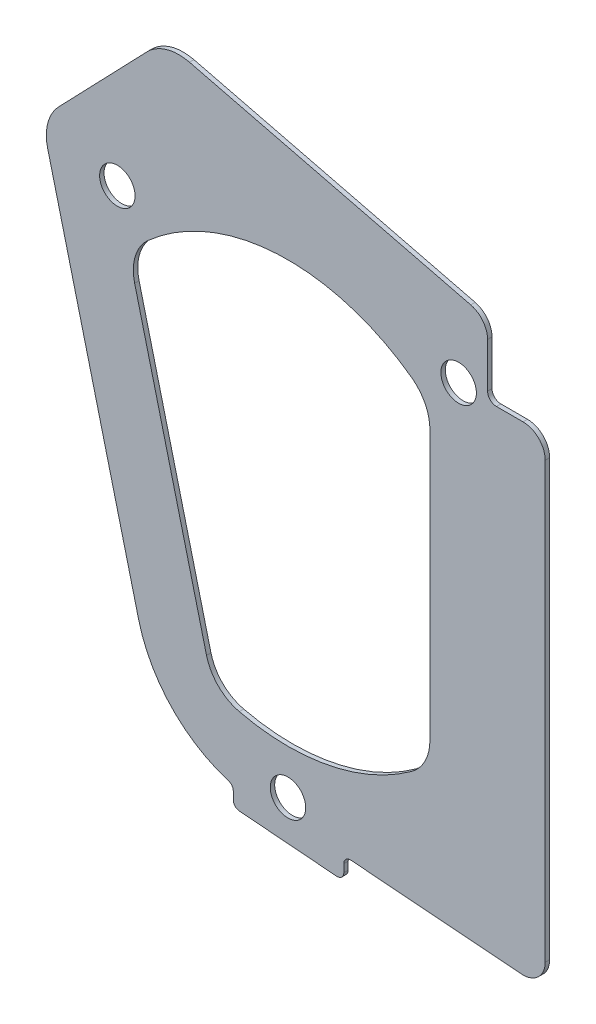
SolidWorks part; units mm, degrees
ref_plane "Front Plane" through (0, 0, 0) normal (0, 0, 1) x (1, 0, 0)
ref_plane "Top Plane" through (0, 0, 0) normal (0, 1, 0) x (1, 0, 0)
ref_plane "Right Plane" through (0, 0, 0) normal (1, 0, 0) x (0, 0, -1)
sketch "Sketch1" plane through (0, 0, 0) normal (0, 0, 1) x (1, 0, 0)
  line L0 (-38.475, 42.7308) -> (0, 0) construction
  line L1 (0, 0) -> (0, 57.5) construction
  line L4 (32, 30.3686) -> (32, -30.3686)
  line L5 (-12.3399, -62.3721) -> (-12.3399, -64.1252)
  line L6 (-10.9599, -65.6204) -> (10.9599, -67.3796)
  line L7 (12.5799, -65.8844) -> (12.5799, -64.1313)
  line L8 (14.1967, -62.6359) -> (52.6107, -65.6359)
  line L9 (58, -60.6511) -> (58, 37.3641)
  line L10 (53, 42.3641) -> (47, 42.3641)
  line L11 (45, 44.3641) -> (45, 54.4497)
  line L12 (41.2, 59.3036) -> (-22.2032, 74.9785)
  line L14 (-12.3399, -61.2431) -> (-9.4422, -62.0196) construction
  line L15 (-31.8103, 72.2031) -> (-51.6964, 51.5287)
  line L16 (-54.1884, 42.1617) -> (-33.6727, -39.5692)
  line L17 (-34.5729, 25.6286) -> (-18.3707, -38.9182)
  circle A0 centre (0, 0) radius 57.5 construction
  arc A2 (27.8667, 38.4669) -> (-31.5069, 35.5467) centre (0, 0) ccw
  circle A3 centre (0, -57.5) radius 4
  circle A4 centre (-38.475, 42.7308) radius 4
  circle A5 centre (38.475, 42.7308) radius 4
  arc A6 (-33.6727, -39.5692) -> (-13.3988, -60.9385) centre (-4.5754, -32.2653) ccw
  circle A7 centre (0, 0) radius 47.5 construction
  arc A9 (32, -30.3686) -> (27.8667, -38.4669) centre (22, -30.3686) cw
  arc A10 (32, 30.3686) -> (27.8667, 38.4669) centre (22, 30.3686) ccw
  arc A11 (-10.9841, -46.2126) -> (27.8667, -38.4669) centre (0, 0) ccw
  arc A12 (-18.3707, -38.9182) -> (-10.9841, -46.2126) centre (-8.6716, -36.4836) ccw
  arc A13 (-34.5729, 25.6286) -> (-31.5069, 35.5467) centre (-24.8738, 28.0632) cw
  arc A14 (-22.2032, 74.9785) -> (-31.8103, 72.2031) centre (-24.6032, 65.2707) ccw
  arc A15 (-51.6964, 51.5287) -> (-54.1884, 42.1617) centre (-44.4893, 44.5964) ccw
  arc A16 (58, 37.3641) -> (53, 42.3641) centre (53, 37.3641) ccw
  arc A17 (45, 54.4497) -> (41.2, 59.3036) centre (40, 54.4497) ccw
  arc A18 (47, 42.3641) -> (45, 44.3641) centre (47, 44.3641) cw
  arc A19 (52.6107, -65.6359) -> (58, -60.6511) centre (53, -60.6511) ccw
  arc A20 (12.5799, -64.1313) -> (14.1967, -62.6359) centre (14.0799, -64.1313) cw
  arc A21 (10.9599, -67.3796) -> (12.5799, -65.8844) centre (11.0799, -65.8844) ccw
  arc A22 (-12.3399, -64.1252) -> (-10.9599, -65.6204) centre (-10.8399, -64.1252) ccw
  arc A23 (-12.3399, -62.3721) -> (-13.3988, -60.9385) centre (-13.8399, -62.3721) ccw
  point P30 (0, -66.5)
  point P39 (-17.007, -44.351)
  point P44 (-27.808, 76.3641)
  point P47 (-55.5373, 47.5355)
  point P50 (58, 42.3641)
  point P53 (45, 58.3641)
  point P56 (45, 42.3641)
  point P59 (58, -66.0568)
  point P62 (12.5799, -62.5096)
  point P65 (12.5799, -67.5096)
  point P68 (-12.3399, -65.5096)
  dimension "D1" = 115
  dimension "D4" = 8
  dimension "D8" = 58
  dimension "D9" = 10
  dimension "D18" = 30
  dimension "D23" = 10
  dimension "D24" = 10
  dimension "D25" = 5
  dimension "D26" = 2
  dimension "D27" = 5
  dimension "D28" = 1.5
  dimension "D5" = 42
  dimension "D6" = 5
  dimension "D7" = 32
  dimension "D2" = 25
  dimension "D10" = 13
  dimension "D11" = 108
  dimension "D12" = 9
  dimension "D13" = 2
  dimension "D14" = 16
  dimension "D15" = 18
  dimension "D16" = 3
  dimension "D17" = 75
  dimension "D19" = 75
  dimension "D20" = 40
  dimension "D21" = 120
  dimension "D22" = 15
  dimension "D29" = 3
  dimension "D3" = 10
extrude "Bumper link" add sketch "Sketch1" along normal blind 1
